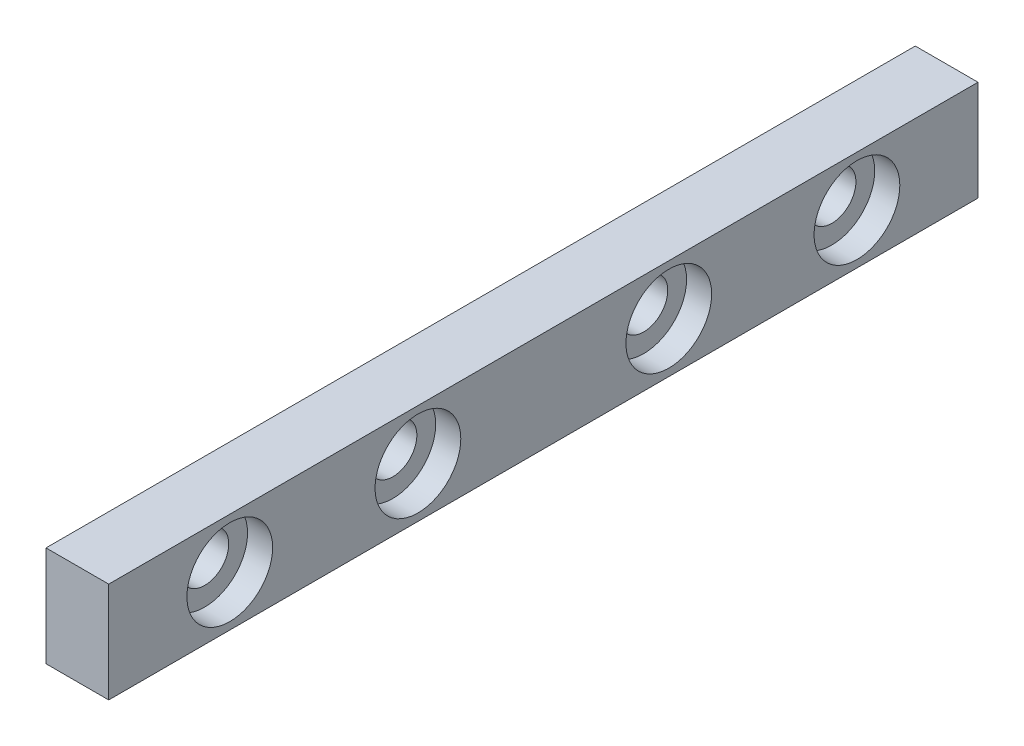
SolidWorks part; units mm, degrees
ref_plane "前视基准面" through (0, 0, 0) normal (0, 0, 1) x (1, 0, 0)
ref_plane "上视基准面" through (0, 0, 0) normal (0, 1, 0) x (1, 0, 0)
ref_plane "右视基准面" through (0, 0, 0) normal (1, 0, 0) x (0, 0, -1)
other "Configuration Table"
sketch "草图1" plane through (0, 0, 0) normal (1, 0, 0) x (0, 0, -1)
  line L0 (0, 2.4) -> (41.58, 2.4) construction
  line L1 (0, 0) -> (41.58, 0)
  line L2 (0, 0) -> (0, 4.8)
  line L3 (0, 4.8) -> (41.58, 4.8)
  line L4 (41.58, 0) -> (41.58, 4.8)
  line L5 (20.79, 4.8) -> (20.79, 0) construction
  circle A0 centre (14.79, 2.4) radius 1.15
  circle A1 centre (5.79, 2.4) radius 1.15
  circle A2 centre (26.79, 2.4) radius 1.15
  circle A3 centre (35.79, 2.4) radius 1.15
  dimension "D3" = 6
  dimension "D5" = 2.3
  dimension "D1" = 4.8
  dimension "D2" = 41.58
  dimension "D4" = 15
extrude "凸台-拉伸1" add sketch "草图1" along normal blind 3
sketch "草图2" plane through (3, 0, 0) normal (1, 0, 0) x (0, 0, -1)
  circle A0 centre (5.79, 2.4) radius 2.05
  circle A1 centre (14.79, 2.4) radius 2.05
  circle A2 centre (26.79, 2.4) radius 2.05
  circle A3 centre (35.79, 2.4) radius 2.05
  dimension "D1" = 4.1
extrude "切除-拉伸1" cut sketch "草图2" against normal blind 1.2
